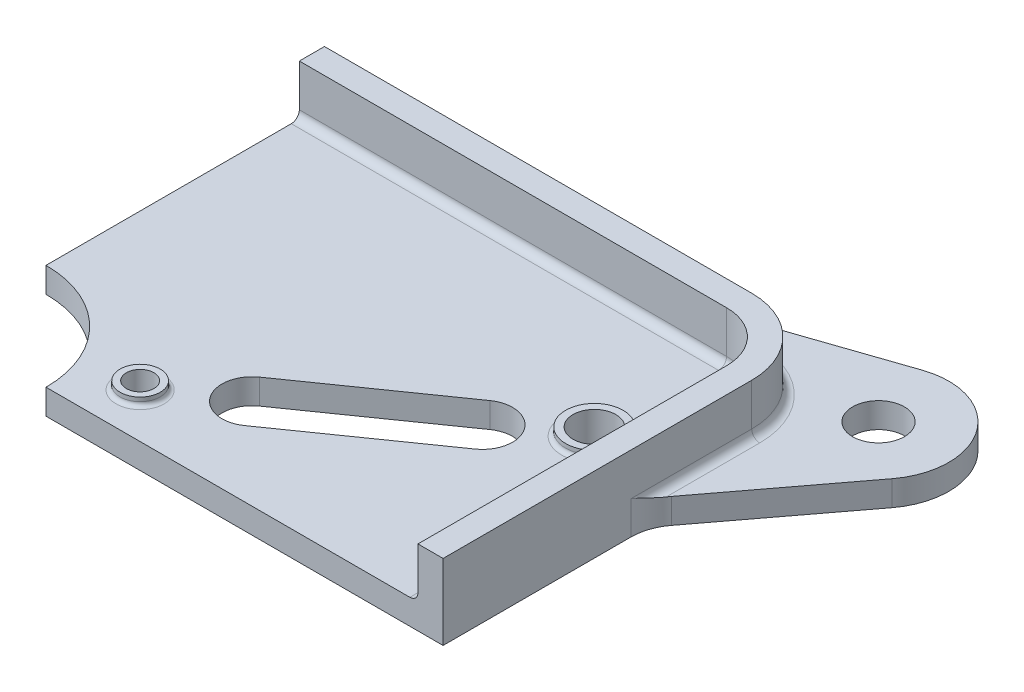
SolidWorks part; units mm, degrees
ref_plane "Front Plane" through (0, 0, 0) normal (0, 0, 1) x (1, 0, 0)
ref_plane "Top Plane" through (0, 0, 0) normal (0, 1, 0) x (1, 0, 0)
ref_plane "Right Plane" through (0, 0, 0) normal (1, 0, 0) x (0, 0, -1)
sketch "Sketch1" plane through (0, 0, 0) normal (0, 1, 0) x (1, 0, 0)
  line L0 (0, 0) -> (24.1147, 16.8853) construction
  line L1 (13.335, 0) -> (63.5, 0)
  line L2 (0, 13.335) -> (0, 48.514)
  line L3 (0, 48.514) -> (53.975, 48.514)
  line L4 (63.5, 0) -> (63.5, 38.989)
  line L5 (24.1147, 16.8853) -> (41.2238, 28.8652) construction
  line L7 (25.7173, 14.5966) -> (42.8264, 26.5765)
  line L8 (30.0879, 8.3546) -> (47.1971, 20.3346)
  arc A0 (53.975, 48.514) -> (63.5, 38.989) centre (53.975, 38.989) cw
  arc A1 (13.335, 0) -> (0, 13.335) centre (0, 0) ccw
  arc A2 (25.7173, 14.5966) -> (30.0879, 8.3546) centre (27.9026, 11.4756) ccw
  arc A3 (47.1971, 20.3346) -> (42.8264, 26.5765) centre (45.0117, 23.4556) ccw
  point P7 (63.5, 48.514)
  dimension "D3" = 9.525
  dimension "D4" = 35
  dimension "D1" = 63.5
  dimension "D2" = 48.514
  dimension "D5" = 29.4386
  dimension "D6" = 20.8864
extrude "Extrude1" add sketch "Sketch1" along normal blind 9.525
shell "Shell1" thickness 3.175
sketch "Sketch4" plane through (0, 0, 0) normal (0, 1, 0) x (1, 0, 0)
  line L0 (0, 0) -> (69.7016, 48.8056) construction
  line L1 (0, 0) -> (70.8304, 0) construction
  line L2 (0, 48.514) -> (0, 77.7815) construction
  line L3 (41.3258, 48.514) -> (41.3258, 77.7815) construction
  line L4 (63.5, 0) -> (91.3132, 0) construction
  line L5 (63.5, 25.8572) -> (91.3132, 25.8572) construction
  line L6 (41.3258, 48.514) -> (66.83, 57.219)
  line L7 (63.5, 25.8572) -> (76.7937, 43.4451)
  line L8 (53.975, 48.514) -> (0, 48.514) construction
  line L9 (53.975, 48.514) -> (41.3258, 48.514)
  line L10 (63.5, 0) -> (63.5, 38.989) construction
  line L11 (63.5, 25.8572) -> (63.5, 38.989)
  arc A0 (76.7937, 43.4451) -> (66.83, 57.219) centre (69.7016, 48.8056) ccw
  circle A1 centre (69.7016, 48.8056) radius 3.2729
  arc A2 (63.5, 38.989) -> (53.975, 48.514) centre (53.975, 38.989) ccw construction
  arc A3 (63.5, 38.989) -> (53.975, 48.514) centre (53.975, 38.989) ccw
  dimension "D3" = 17.78
  dimension "D1" = 35
  dimension "D2" = 85.09
  dimension "D4" = 41.3258
  dimension "D5" = 25.8572
extrude "Extrude2" add sketch "Sketch4" along normal blind 3.175
fillet "Fillet1" radius 6.35 2 edges at (41.3258, 1.5875, -48.514) (63.5, 1.5875, -25.8572)
fillet "Fillet2" radius 1.016 6 edges at (47.1235, 3.175, -48.514) (26.9875, 3.175, -45.339) (58.4651, 3.175, -43.4791) (60.325, 3.175, -19.4945) (60.7102, 3.175, -45.7242) (63.5, 3.175, -31.3582)
ref_plane "Plane3" through (0.1457, 0, 0.2081) normal (0.5736, 0, 0.8192) x (0.8192, 0, -0.5736)
ref_plane "Plane4" through (0, 4.191, 0) normal (0, 1, 0) x (-1, 0, 0)
sketch "Sketch5" plane through (0, 4.191, 0) normal (0, 1, 0) x (-1, 0, 0)
  circle A1 centre (-53.3343, -29.2831) radius 3.6336
  circle A2 centre (-19.58, -5.6481) radius 2.54
  dimension "D1" = 5.08
extrude "Extrude3" add sketch "Sketch5" against normal up to body
sketch "Sketch6" plane through (0, 4.191, 0) normal (0, 1, 0) x (-1, 0, 0)
  circle A0 centre (-53.3343, -29.2831) radius 2.7088
  circle A1 centre (-19.58, -5.6481) radius 1.7399
  dimension "D1" = 3.4798
extrude "Extrude4" cut sketch "Sketch6" against normal through all
fillet "Fillet3" radius 0.508 2 edges at (53.3343, 3.175, -32.9167) (19.58, 3.175, -8.1881)
